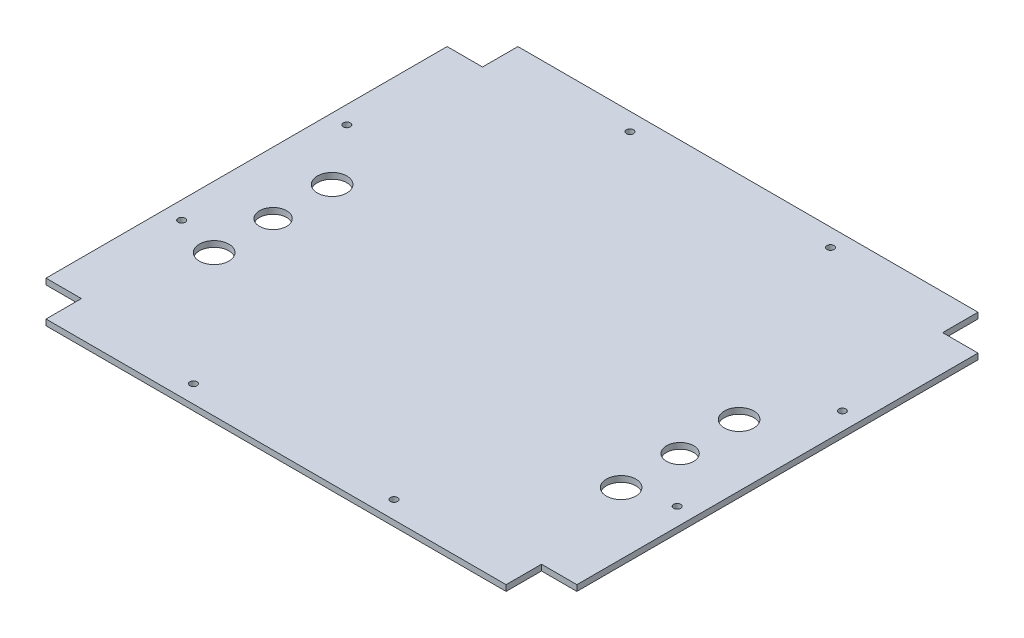
SolidWorks part; units mm, degrees
ref_plane "Alzado" through (0, 0, 0) normal (0, 0, 1) x (1, 0, 0)
ref_plane "Planta" through (0, 0, 0) normal (0, 1, 0) x (1, 0, 0)
ref_plane "Vista lateral" through (0, 0, 0) normal (1, 0, 0) x (0, 0, -1)
sketch "Croquis1" plane through (0, 0, 0) normal (0, 1, 0) x (1, 0, 0)
  line L1 (-158.3268, 165.9821) -> (231.6732, 165.9821)
  line L2 (-188.3268, 135.9821) -> (-188.3268, -204.0179)
  line L3 (-158.3268, -234.0179) -> (231.6732, -234.0179)
  line L4 (261.6732, 135.9821) -> (261.6732, -204.0179)
  line L7 (-188.3268, 135.9821) -> (-158.3268, 135.9821)
  line L8 (-158.3268, 165.9821) -> (-158.3268, 135.9821)
  line L11 (261.6732, 135.9821) -> (231.6732, 135.9821)
  line L12 (231.6732, 165.9821) -> (231.6732, 135.9821)
  line L15 (-188.3268, -204.0179) -> (-158.3268, -204.0179)
  line L16 (-158.3268, -234.0179) -> (-158.3268, -204.0179)
  line L19 (261.6732, -204.0179) -> (231.6732, -204.0179)
  line L20 (231.6732, -234.0179) -> (231.6732, -204.0179)
  circle A0 centre (-173.3268, 35.9821) radius 3
  circle A1 centre (-173.3268, -104.0179) radius 3
  circle A2 centre (-48.3268, 150.9821) radius 3
  circle A3 centre (121.6732, 150.9821) radius 3
  circle A4 centre (246.6732, 35.9821) radius 3
  circle A5 centre (246.6732, -104.0179) radius 3
  circle A6 centre (-48.3268, -219.0179) radius 3
  circle A7 centre (121.6732, -219.0179) radius 3
  circle A8 centre (-135.8268, -64.0179) radius 11.5
  circle A9 centre (-135.8268, -114.0179) radius 12.5
  circle A10 centre (-135.8268, -14.0179) radius 12.5
  circle A11 centre (209.1732, -114.0179) radius 12.5
  circle A12 centre (209.1732, -64.0179) radius 11.5
  circle A13 centre (209.1732, -14.0179) radius 12.5
  dimension "D3" = 30
  dimension "D4" = 30
  dimension "D5" = 30
  dimension "D6" = 30
  dimension "D7" = 30
  dimension "D8" = 30
  dimension "D14" = 100
  dimension "D15" = 100
  dimension "D11" = 6
  dimension "D24" = 6
  dimension "D25" = 6
  dimension "D26" = 6
  dimension "D27" = 6
  dimension "D28" = 6
  dimension "D29" = 6
  dimension "D30" = 6
  dimension "D32" = 23
  dimension "D33" = 25
  dimension "D34" = 25
  dimension "D9" = 30
  dimension "D10" = 30
  dimension "D12" = 110
  dimension "D13" = 110
  dimension "D16" = 100
  dimension "D17" = 100
  dimension "D18" = 110
  dimension "D19" = 110
  dimension "D20" = 15
  dimension "D21" = 15
  dimension "D22" = 15
  dimension "D23" = 15
  dimension "D31" = 37.5
  dimension "D35" = 50
  dimension "D36" = 50
  dimension "D37" = 170
  dimension "D38" = 390
  dimension "D39" = 37.5
extrude "Saliente-Extruir1" add sketch "Croquis1" along normal blind 5
